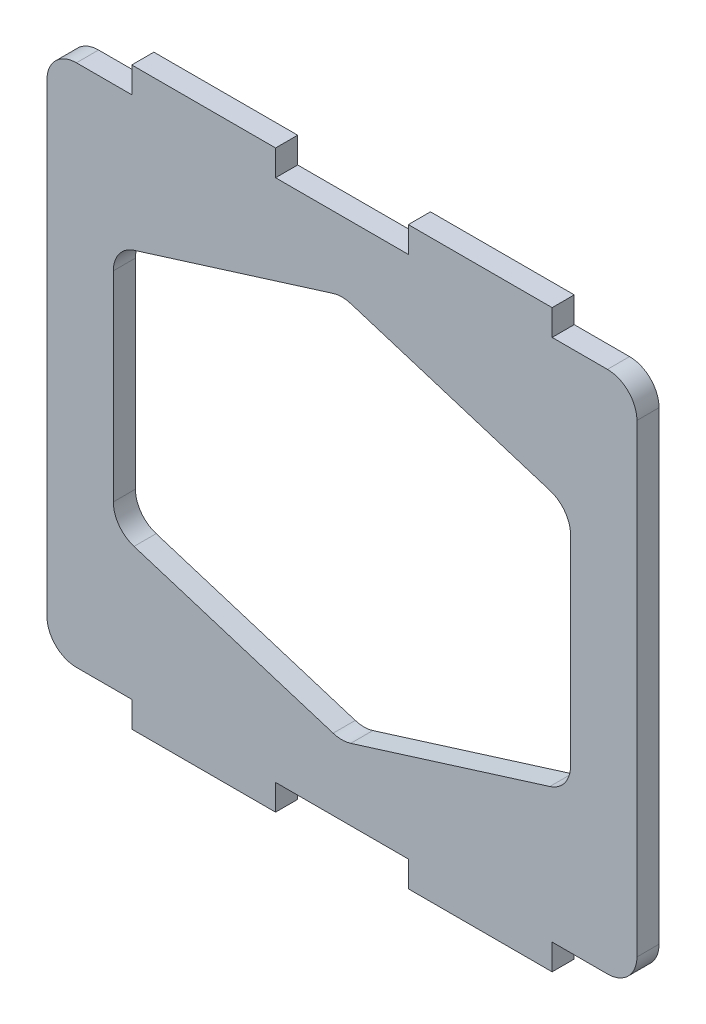
SolidWorks part; units mm, degrees
ref_plane "Front Plane" through (0, 0, 0) normal (0, 0, 1) x (1, 0, 0)
ref_plane "Top Plane" through (0, 0, 0) normal (0, 1, 0) x (1, 0, 0)
ref_plane "Right Plane" through (0, 0, 0) normal (1, 0, 0) x (0, 0, -1)
sketch "Sketch1" plane through (0, 0, 0) normal (0, 0, 1) x (1, 0, 0)
  line L0 (18, 17.75) -> (14.25, 17.75)
  line L1 (14.25, 17.75) -> (14.25, 19.5)
  line L2 (14.25, 19.5) -> (4.5, 19.5)
  line L3 (4.5, 19.5) -> (4.5, 17.75)
  line L4 (4.5, 17.75) -> (-4.5, 17.75)
  line L5 (-4.5, 17.75) -> (-4.5, 19.5)
  line L6 (-4.5, 19.5) -> (-14.25, 19.5)
  line L7 (-14.25, 19.5) -> (-14.25, 17.75)
  line L8 (-14.25, 17.75) -> (-18, 17.75)
  line L9 (-20, 15.75) -> (-20, -15.75)
  line L10 (-18, -17.75) -> (-14.25, -17.75)
  line L11 (-14.25, -17.75) -> (-14.25, -19.5)
  line L12 (-14.25, -19.5) -> (-4.5, -19.5)
  line L13 (-4.5, -19.5) -> (-4.5, -17.75)
  line L14 (-4.5, -17.75) -> (4.5, -17.75)
  line L15 (4.5, -17.75) -> (4.5, -19.5)
  line L16 (4.5, -19.5) -> (14.25, -19.5)
  line L17 (14.25, -19.5) -> (14.25, -17.75)
  line L18 (14.25, -17.75) -> (18, -17.75)
  line L19 (20, -15.75) -> (20, 15.75)
  line L20 (-0.5961, -12.9091) -> (-14.0961, -8.6936)
  line L21 (-15.5, -6.7845) -> (-15.5, 6.7845)
  line L22 (-14.0961, 8.6936) -> (-0.5961, 12.9091)
  line L23 (0.5961, 12.9091) -> (14.0961, 8.6936)
  line L24 (15.5, 6.7845) -> (15.5, -6.7845)
  line L25 (14.0961, -8.6936) -> (0.5961, -12.9091)
  arc A0 (20, 15.75) -> (18, 17.75) centre (18, 15.75) ccw
  arc A1 (-18, 17.75) -> (-20, 15.75) centre (-18, 15.75) ccw
  arc A2 (-20, -15.75) -> (-18, -17.75) centre (-18, -15.75) ccw
  arc A3 (18, -17.75) -> (20, -15.75) centre (18, -15.75) ccw
  arc A4 (0.5961, -12.9091) -> (-0.5961, -12.9091) centre (0, -11) cw
  arc A5 (-14.0961, -8.6936) -> (-15.5, -6.7845) centre (-13.5, -6.7845) cw
  arc A6 (-15.5, 6.7845) -> (-14.0961, 8.6936) centre (-13.5, 6.7845) cw
  arc A7 (-0.5961, 12.9091) -> (0.5961, 12.9091) centre (0, 11) cw
  arc A8 (14.0961, 8.6936) -> (15.5, 6.7845) centre (13.5, 6.7845) cw
  arc A9 (15.5, -6.7845) -> (14.0961, -8.6936) centre (13.5, -6.7845) cw
extrude "fpv-plate" add sketch "Sketch1" against normal blind 1.5
